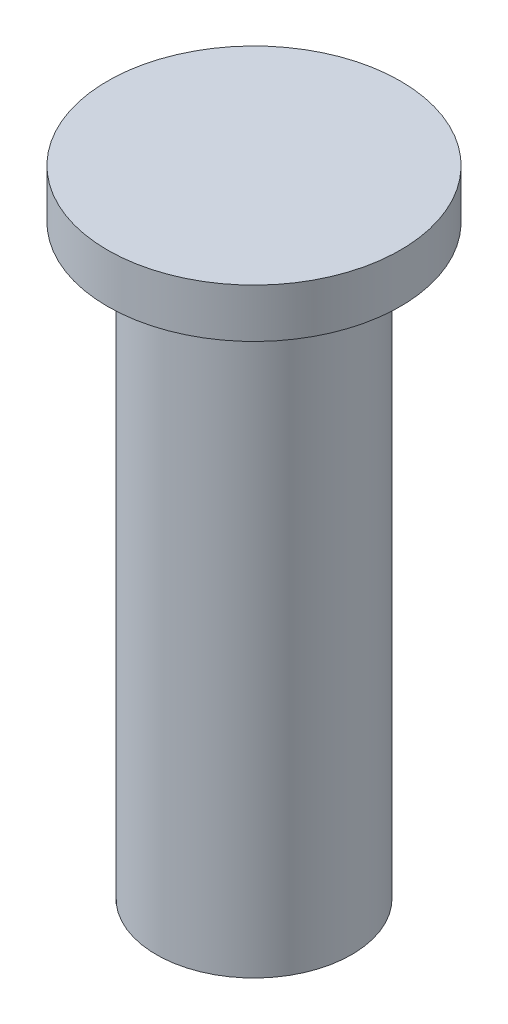
SolidWorks part; units mm, degrees
ref_plane "Front Plane" through (0, 0, 0) normal (0, 0, 1) x (1, 0, 0)
ref_plane "Top Plane" through (0, 0, 0) normal (0, 1, 0) x (1, 0, 0)
ref_plane "Right Plane" through (0, 0, 0) normal (1, 0, 0) x (0, 0, -1)
sketch "Sketch1" plane through (0, 0, 0) normal (0, 1, 0) x (1, 0, 0)
  circle A0 centre (0, 0) radius 12.7
extrude "Boss-Extrude1" add sketch "Sketch1" along normal blind 76.2
sketch "Sketch2" plane through (0, 76.2, 0) normal (0, 1, 0) x (1, 0, 0)
  circle A0 centre (0, 0) radius 19.05
extrude "Boss-Extrude2" add sketch "Sketch2" along normal blind 6.35
